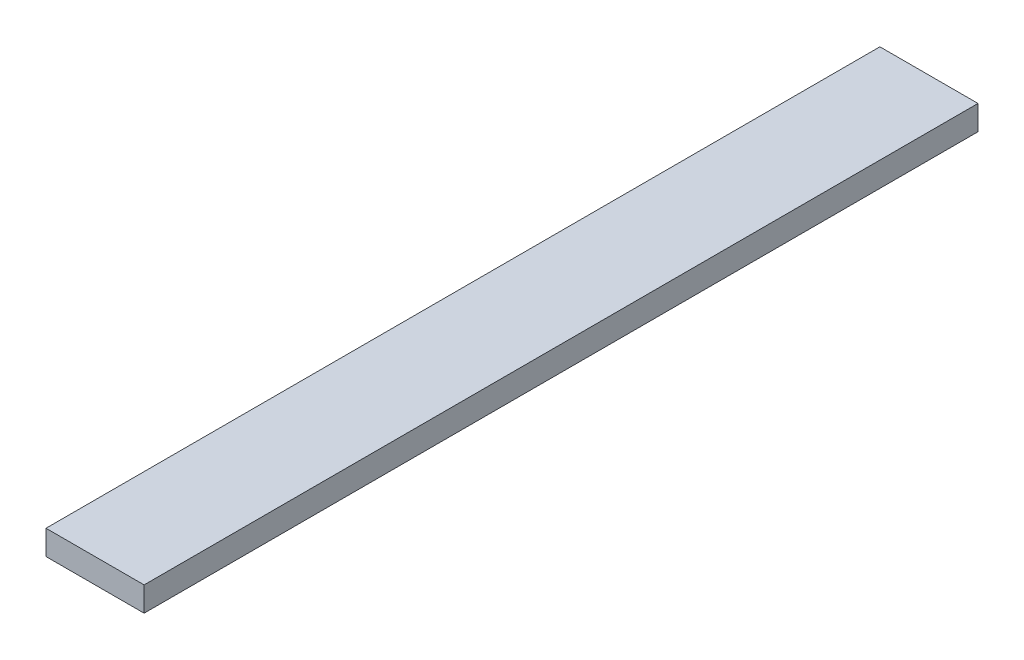
SolidWorks part; units mm, degrees
ref_plane "Płaszczyzna przednia" through (0, 0, 0) normal (0, 0, 1) x (1, 0, 0)
ref_plane "Płaszczyzna górna" through (0, 0, 0) normal (0, 1, 0) x (1, 0, 0)
ref_plane "Płaszczyzna prawa" through (0, 0, 0) normal (1, 0, 0) x (0, 0, -1)
sketch "Szkic1" plane through (0, 0, 0) normal (0, 1, 0) x (1, 0, 0)
  line L1 (-10, -85) -> (10, -85)
  line L2 (-10, -85) -> (-10, 85)
  line L3 (-10, 85) -> (10, 85)
  line L4 (10, -85) -> (10, 85)
  line L5 (0, 85) -> (0, -85) construction
  line L6 (-10, 0) -> (10, 0) construction
  point P0 (0, 0)
  dimension "D1" = 170
  dimension "D2" = 20
extrude "Dodanie-wyciągnięcie1" add sketch "Szkic1" along normal blind 5
